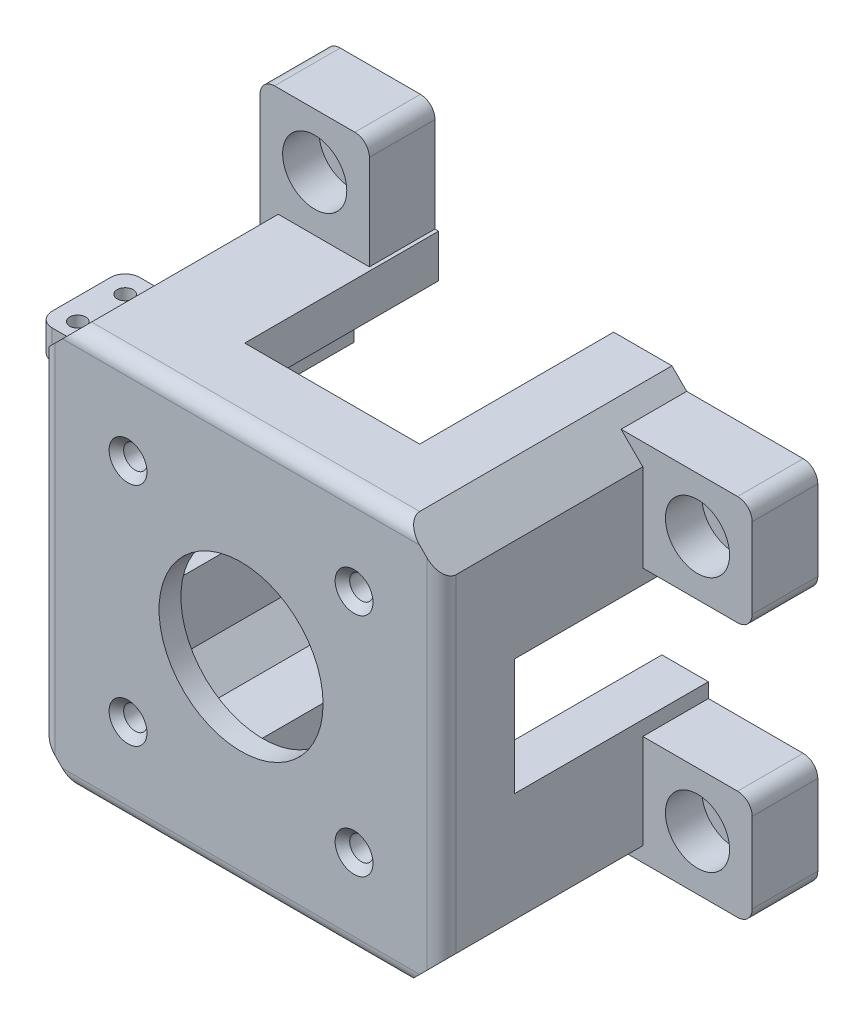
SolidWorks part; units mm, degrees
ref_plane "Front Plane" through (0, 0, 0) normal (0, 0, 1) x (1, 0, 0)
ref_plane "Top Plane" through (0, 0, 0) normal (0, 1, 0) x (1, 0, 0)
ref_plane "Right Plane" through (0, 0, 0) normal (1, 0, 0) x (0, 0, -1)
sketch "Sketch2" plane through (0, 0, 0) normal (0, 0, 1) x (1, 0, 0)
  line L1 (-27.5, -27.0238) -> (27.5, -27.0238)
  line L2 (-27.5, -27.0238) -> (-27.5, 27.9762)
  line L3 (-27.5, 27.9762) -> (27.5, 27.9762)
  line L4 (27.5, -27.0238) -> (27.5, 27.9762)
  line L5 (-27.5, -27.0238) -> (27.5, 27.9762) construction
  line L6 (-27.5, 27.9762) -> (27.5, -27.0238) construction
  line L16 (21.1184, 17.2806) -> (17.2806, 21.1184)
  line L17 (17.2806, 21.1184) -> (-17.2806, 21.1184)
  line L18 (-17.2806, 21.1184) -> (-21.1184, 17.2806)
  line L19 (-21.1184, 17.2806) -> (-21.1184, -17.2806)
  line L20 (-21.1184, -17.2806) -> (-17.2806, -21.1184)
  line L21 (-17.2806, -21.1184) -> (17.2806, -21.1184)
  line L22 (17.2806, -21.1184) -> (21.1184, -17.2806)
  line L23 (21.1184, -17.2806) -> (21.1184, 17.2806)
  circle A2 centre (0, 0.4762) radius 16.593
  dimension "D1" = 55
  dimension "D2" = 55
extrude "Boss-Extrude1" add sketch "Sketch2" along normal blind 33.6 contours L1 L4 L3 L2 L23 L22 L21 L20 L19 L18 L17 L16
sketch "Sketch3" plane through (0, 0, 33.6) normal (0, 0, 1) x (1, 0, 0)
  line L0 (-27.5, 27.9762) -> (27.5, -27.0238)
  line L1 (-27.5, -27.0238) -> (27.5, -27.0238)
  line L2 (-27.5, -27.0238) -> (-27.5, 27.9762)
  line L3 (-27.5, 27.9762) -> (27.5, 27.9762)
  line L4 (27.5, -27.0238) -> (27.5, 27.9762)
  line L5 (27.5, 27.9762) -> (-27.5, -27.0238)
  circle A0 centre (0, 0.4762) radius 11.25
  line M1 (21.1184, 17.2806) -> (21.1184, -17.2806)
  line M2 (21.1184, -17.2806) -> (17.2806, -21.1184)
  line M3 (17.2806, -21.1184) -> (-17.2806, -21.1184)
  line M4 (-17.2806, -21.1184) -> (-21.1184, -17.2806)
  line M5 (-21.1184, -17.2806) -> (-21.1184, 17.2806)
  line M6 (-21.1184, 17.2806) -> (-17.2806, 21.1184)
  line M7 (-17.2806, 21.1184) -> (17.2806, 21.1184)
  line M8 (17.2806, 21.1184) -> (21.1184, 17.2806)
  line M9 (-27.5, -27.0238) -> (27.5, -27.0238)
  line M10 (27.5, -27.0238) -> (27.5, 27.9762)
  line M11 (27.5, 27.9762) -> (-27.5, 27.9762)
  line M12 (-27.5, 27.9762) -> (-27.5, -27.0238)
  dimension "D1" = 22.5
extrude "Boss-Extrude2" add sketch "Sketch3" along normal blind 3 contours A0 L0 L5 M6 M5 M4 | A0 L5 L0 M4 M3 M2 | A0 L0 L5 M2 M1 M8 | A0 L5 L0 M8 M7 M6 | L5 L0 M4 M5 M6 M12 | L5 L0 M4 M9 M2 M3 | L5 L0 M10 M8 M1 M2 | L5 L0 M11 M6 M7 M8
sketch "Sketch4" plane through (0, 0, 0) normal (0, 0, -1) x (-1, 0, 0)
  line L0 (0, 0) -> (-27.5, 0)
  line L1 (-27.5, -27.0238) -> (-27.5, 27.9762) construction
  line L2 (-27.5, 0) -> (-27.5, 10)
  line L3 (0, 0) -> (0, 34.2278) construction
  line L4 (-27.5, 10) -> (-42.5, 10)
  line L5 (-27.5, 10) -> (-27.5, 25)
  line L6 (-27.5, 25) -> (-42.5, 25)
  line L7 (-42.5, 10) -> (-42.5, 25)
  line L8 (42.5, 10) -> (42.5, 25)
  line L9 (27.5, 25) -> (42.5, 25)
  line L10 (27.5, 10) -> (27.5, 25)
  line L11 (27.5, 10) -> (42.5, 10)
  line L16 (-42.5, -10) -> (-42.5, -25)
  line L17 (-27.5, -25) -> (-42.5, -25)
  line L18 (-27.5, -10) -> (-27.5, -25)
  line L19 (-27.5, -10) -> (-42.5, -10)
  line L20 (27.5, -27.0238) -> (-27.5, -27.0238) construction
  line L21 (25, -27.0238) -> (10, -27.0238)
  line L22 (25, -27.0238) -> (25, -42.0238)
  line L23 (25, -42.0238) -> (10, -42.0238)
  line L24 (10, -27.0238) -> (10, -42.0238)
  circle A1 centre (-35, 17.5) radius 2.6
  circle A2 centre (35, 17.5) radius 2.6
  circle A4 centre (-35, -17.5) radius 2.6
  circle A5 centre (17.5, -34.5238) radius 2.6
  dimension "D1" = 10
  dimension "D4" = 5.2
  dimension "D5" = 7.5
  dimension "D10" = 5.2
  dimension "D2" = 15
  dimension "D3" = 15
  dimension "D6" = 7.5
  dimension "D7" = 15
  dimension "D8" = 15
  dimension "D9" = 10
  dimension "D11" = 7.5
  dimension "D12" = 7.5
extrude "Boss-Extrude3" add sketch "Sketch4" against normal blind 9 contours L7 L4 L11 L6 A1 | L11 L19 L16 L17 A4 | A5 | A2 | L22 L23 L24 L21
sketch "Sketch6" plane through (0, 0, 9) normal (0, 0, 1) x (1, 0, 0)
  line L2 (20.955, 0) -> (-20.955, 0) construction
  line L7 (-10, -27.0238) -> (-25, -27.0238)
  line L8 (-25, -27.0238) -> (-25, -42.0238)
  line L9 (-25, -42.0238) -> (-10, -42.0238)
  line L10 (-10, -42.0238) -> (-10, -27.0238)
  line L11 (-10, -27.0238) -> (-25, -27.0238)
  line L12 (-25, -27.0238) -> (-25, -42.0238)
  line L13 (-25, -42.0238) -> (-10, -42.0238)
  line L14 (-10, -42.0238) -> (-10, -27.0238)
  circle A0 centre (35, -17.5) radius 4.4
  circle A2 centre (35, 17.5) radius 4.4
  circle A3 centre (-35, 17.5) radius 4.4
  circle A4 centre (-17.5, -34.5238) radius 4.4
  circle M5 centre (35, -17.5) radius 2.6
  dimension "D1" = 8.8
  dimension "D3" = 8.8
  dimension "D2" = 0
extrude "Cut-Extrude1" cut sketch "Sketch6" against normal blind 5 contours A4 | A3 | A0 M5 | A2
chamfer "Chamfer1" distance 5 angle 45 4 edges at (27.5, -27.0238, 18.3) (-27.5, -27.0238, 18.3) (27.5, 27.9762, 18.3) (-27.5, 27.9762, 18.3)
fillet "Fillet4" radius 2 12 edges at (42.5, -10, 4.5) (42.5, -25, 4.5) (42.5, 10, 4.5) (42.5, 25, 4.5) (-42.5, 10, 4.5) (-42.5, 25, 4.5) (0, -27.0238, 36.6) (-27.5, 0.4762, 36.6) (27.5, 0.4762, 36.6) (0, 27.9762, 36.6) (-25, -42.0238, 4.5) (-10, -42.0238, 4.5)
sketch "Sketch7" plane through (0, -27.0238, 0) normal (0, -1, 0) x (1, 0, 0)
  line L0 (-10, 0) -> (22.5, 0) construction
  line L1 (-9.5, 0) -> (14.5, 0)
  line L2 (-9.5, 0) -> (-9.5, 26.6)
  line L3 (-9.5, 26.6) -> (14.5, 26.6)
  line L4 (14.5, 0) -> (14.5, 26.6)
  line L5 (22.5, 0) -> (22.5, 34.6) construction
  line L6 (-22.5, 34.6) -> (-22.5, 9) construction
  line L7 (22.5, 34.6) -> (-22.5, 34.6) construction
  dimension "D1" = 8
  dimension "D2" = 13
  dimension "D3" = 8
extrude "Cut-Extrude2" cut sketch "Sketch7" against normal blind 67
sketch "Sketch8" plane through (-27.5, 0, 0) normal (-1, 0, 0) x (0, 0, 1)
  line L0 (34.6, -22.0238) -> (34.6, 22.9762) construction
  line L1 (0, 8) -> (26.6, 8)
  line L2 (0, 8) -> (0, -8)
  line L3 (0, -8) -> (26.6, -8)
  line L4 (26.6, 8) -> (26.6, -8)
  dimension "D1" = 8
  dimension "D2" = 16
  dimension "D3" = 26.6
  dimension "D4" = 8
extrude "Cut-Extrude3" cut sketch "Sketch8" against normal blind 67
sketch "Sketch9" plane through (0, 0, 0) normal (0, 0, -1) x (-1, 0, 0)
  line L0 (-21.1184, -17.2806) -> (-21.1184, -8) construction
  line L1 (-21.1184, -8) -> (-27.5, -8) construction
  line L2 (-27.5, -8) -> (-27.5, -10) construction
  line L3 (-27.5, -10) -> (-40.5, -10) construction
  line L4 (-42.5, -12) -> (-42.5, -23) construction
  line L5 (-40.5, -25) -> (-24.5238, -25) construction
  line L6 (-24.5238, -25) -> (-22.5, -27.0238) construction
  line L7 (-22.5, -27.0238) -> (-14.5, -27.0238) construction
  line L8 (-14.5, -27.0238) -> (-14.5, -21.1184) construction
  line L9 (-14.5, -21.1184) -> (-17.2806, -21.1184) construction
  line L10 (-17.2806, -21.1184) -> (-21.1184, -17.2806) construction
  line L11 (27.5, -22.0238) -> (27.5, -8) construction
  line L12 (27.5, -8) -> (21.1184, -8) construction
  line L13 (21.1184, -8) -> (21.1184, -17.2806) construction
  line L14 (21.1184, -17.2806) -> (17.2806, -21.1184) construction
  line L15 (17.2806, -21.1184) -> (9.5, -21.1184) construction
  line L16 (9.5, -21.1184) -> (9.5, -27.0238) construction
  line L17 (9.5, -27.0238) -> (10, -27.0238) construction
  line L18 (10, -27.0238) -> (10, -40.0238) construction
  line L19 (12, -42.0238) -> (23, -42.0238) construction
  line L20 (25, -40.0238) -> (25, -24.5238) construction
  line L21 (25, -24.5238) -> (27.5, -22.0238) construction
  line L22 (21.1184, 17.2806) -> (21.1184, 8) construction
  line L23 (21.1184, 8) -> (27.5, 8) construction
  line L24 (27.5, 8) -> (27.5, 10) construction
  line L25 (27.5, 10) -> (40.5, 10) construction
  line L26 (42.5, 12) -> (42.5, 23) construction
  line L27 (40.5, 25) -> (25.4762, 25) construction
  line L28 (25.4762, 25) -> (22.5, 27.9762) construction
  line L29 (22.5, 27.9762) -> (9.5, 27.9762) construction
  line L30 (9.5, 27.9762) -> (9.5, 21.1184) construction
  line L31 (9.5, 21.1184) -> (17.2806, 21.1184) construction
  line L32 (17.2806, 21.1184) -> (21.1184, 17.2806) construction
  line L33 (-27.5, 10) -> (-27.5, 8) construction
  line L34 (-27.5, 8) -> (-21.1184, 8) construction
  line L35 (-21.1184, 8) -> (-21.1184, 17.2806) construction
  line L36 (-21.1184, 17.2806) -> (-17.2806, 21.1184) construction
  line L37 (-17.2806, 21.1184) -> (-14.5, 21.1184) construction
  line L38 (-14.5, 21.1184) -> (-14.5, 27.9762) construction
  line L39 (-14.5, 27.9762) -> (-22.5, 27.9762) construction
  line L40 (-22.5, 27.9762) -> (-25.4762, 25) construction
  line L41 (-25.4762, 25) -> (-40.5, 25) construction
  line L42 (-42.5, 23) -> (-42.5, 12) construction
  line L43 (-40.5, 10) -> (-27.5, 10) construction
  line L44 (-21.1184, -17.2806) -> (-21.1184, -8)
  line L45 (-21.1184, -8) -> (-27.5, -8)
  line L46 (-27.5, -8) -> (-27.5, -10)
  line L47 (-27.5, -10) -> (-40.5, -10)
  line L48 (-42.5, -12) -> (-42.5, -23)
  line L49 (-40.5, -25) -> (-24.5238, -25)
  line L50 (-24.5238, -25) -> (-22.5, -27.0238)
  line L51 (-22.5, -27.0238) -> (-14.5, -27.0238)
  line L52 (-14.5, -27.0238) -> (-14.5, -21.1184)
  line L53 (-14.5, -21.1184) -> (-17.2806, -21.1184)
  line L54 (-17.2806, -21.1184) -> (-21.1184, -17.2806)
  line L55 (27.5, -22.0238) -> (27.5, -8)
  line L56 (27.5, -8) -> (21.1184, -8)
  line L57 (21.1184, -8) -> (21.1184, -17.2806)
  line L58 (21.1184, -17.2806) -> (17.2806, -21.1184)
  line L59 (17.2806, -21.1184) -> (9.5, -21.1184)
  line L60 (9.5, -21.1184) -> (9.5, -27.0238)
  line L61 (9.5, -27.0238) -> (10, -27.0238)
  line L62 (10, -27.0238) -> (10, -40.0238)
  line L63 (12, -42.0238) -> (23, -42.0238)
  line L64 (25, -40.0238) -> (25, -24.5238)
  line L65 (25, -24.5238) -> (27.5, -22.0238)
  line L66 (21.1184, 17.2806) -> (21.1184, 8)
  line L67 (21.1184, 8) -> (27.5, 8)
  line L68 (27.5, 8) -> (27.5, 10)
  line L69 (27.5, 10) -> (40.5, 10)
  line L70 (42.5, 12) -> (42.5, 23)
  line L71 (40.5, 25) -> (25.4762, 25)
  line L72 (25.4762, 25) -> (22.5, 27.9762)
  line L73 (22.5, 27.9762) -> (9.5, 27.9762)
  line L74 (9.5, 27.9762) -> (9.5, 21.1184)
  line L75 (9.5, 21.1184) -> (17.2806, 21.1184)
  line L76 (17.2806, 21.1184) -> (21.1184, 17.2806)
  line L77 (-27.5, 10) -> (-27.5, 8)
  line L78 (-27.5, 8) -> (-21.1184, 8)
  line L79 (-21.1184, 8) -> (-21.1184, 17.2806)
  line L80 (-21.1184, 17.2806) -> (-17.2806, 21.1184)
  line L81 (-17.2806, 21.1184) -> (-14.5, 21.1184)
  line L82 (-14.5, 21.1184) -> (-14.5, 27.9762)
  line L83 (-14.5, 27.9762) -> (-22.5, 27.9762)
  line L84 (-22.5, 27.9762) -> (-25.4762, 25)
  line L85 (-25.4762, 25) -> (-40.5, 25)
  line L86 (-42.5, 23) -> (-42.5, 12)
  line L87 (-40.5, 10) -> (-27.5, 10)
  arc A0 (-40.5, -10) -> (-42.5, -12) centre (-40.5, -12) ccw construction
  arc A1 (-42.5, -23) -> (-40.5, -25) centre (-40.5, -23) ccw construction
  arc A2 (10, -40.0238) -> (12, -42.0238) centre (12, -40.0238) ccw construction
  arc A3 (23, -42.0238) -> (25, -40.0238) centre (23, -40.0238) ccw construction
  arc A4 (40.5, 10) -> (42.5, 12) centre (40.5, 12) ccw construction
  arc A5 (42.5, 23) -> (40.5, 25) centre (40.5, 23) ccw construction
  arc A6 (-40.5, 25) -> (-42.5, 23) centre (-40.5, 23) ccw construction
  arc A7 (-42.5, 12) -> (-40.5, 10) centre (-40.5, 12) ccw construction
  arc A8 (-40.5, -10) -> (-42.5, -12) centre (-40.5, -12) ccw
  arc A9 (-42.5, -23) -> (-40.5, -25) centre (-40.5, -23) ccw
  arc A10 (10, -40.0238) -> (12, -42.0238) centre (12, -40.0238) ccw
  arc A11 (23, -42.0238) -> (25, -40.0238) centre (23, -40.0238) ccw
  arc A12 (40.5, 10) -> (42.5, 12) centre (40.5, 12) ccw
  arc A13 (42.5, 23) -> (40.5, 25) centre (40.5, 23) ccw
  arc A14 (-40.5, 25) -> (-42.5, 23) centre (-40.5, 23) ccw
  arc A15 (-42.5, 12) -> (-40.5, 10) centre (-40.5, 12) ccw
mirror "Mirror2" about plane through (-25, -42.0238, 9) normal (0, 1, 0) of bodies 107
delete or keep bodies "Body-Delete/Keep 1" type delete bodies bodies 107
sketch "Sketch11" plane through (-27.5, 0, 0) normal (-1, 0, 0) x (0, 0, 1)
  line L0 (0, -65.0238) -> (34.6, -65.0238) construction
  line L1 (0, -62.0238) -> (0, -76.0476) construction
  line L2 (34.6, -62.0238) -> (34.6, -107.0238) construction
  line L3 (0, -62.0238) -> (34.6, -62.0238) construction
  line L5 (20, -67.0238) -> (32, -67.0238)
  line L6 (20, -67.0238) -> (20, -63.0238)
  line L7 (20, -63.0238) -> (32, -63.0238)
  line L8 (32, -67.0238) -> (32, -63.0238)
  line L9 (20, -67.0238) -> (32, -63.0238) construction
  line L10 (20, -63.0238) -> (32, -67.0238) construction
  point P8 (26, -65.0238)
  dimension "D1" = 3
  dimension "D2" = 4
  dimension "D3" = 12
  dimension "D4" = 26
extrude "Boss-Extrude4" add sketch "Sketch11" along normal blind 5 and the other way up to next
sketch "Sketch12" plane through (0, -67.0238, 0) normal (0, -1, 0) x (1, 0, 0)
  line L0 (-32.5, 32) -> (-27.5, 32) construction
  line L2 (-32.5, 20) -> (-32.5, 32) construction
  circle A0 centre (-29.5, 29.5) radius 1.1
  circle A1 centre (-29.5, 23) radius 1.1
  dimension "D1" = 2.2
  dimension "D2" = 6.5
  dimension "D3" = 2.5
  dimension "D4" = 3
  dimension "D5" = 3
extrude "Cut-Extrude5" cut sketch "Sketch12" against normal up to surface (4 mm away) up to face at (-30, -63.0238, 26)
fillet "Fillet8" radius 2 2 edges at (-32.5, -65.0238, 32) (-32.5, -65.0238, 20)
sketch "Sketch13" plane through (0, 0, 36.6) normal (0, 0, 1) x (1, 0, 0)
  line L1 (-15.5, -100.0238) -> (15.5, -100.0238) construction
  line L2 (-15.5, -100.0238) -> (-15.5, -69.0238) construction
  line L3 (-15.5, -69.0238) -> (15.5, -69.0238) construction
  line L4 (15.5, -100.0238) -> (15.5, -69.0238) construction
  line L5 (-15.5, -100.0238) -> (15.5, -69.0238) construction
  line L6 (-15.5, -69.0238) -> (15.5, -100.0238) construction
  circle A0 centre (15.5, -100.0238) radius 1.6
  circle A1 centre (-15.5, -100.0238) radius 1.6
  circle A2 centre (-15.5, -69.0238) radius 1.6
  circle A3 centre (15.5, -69.0238) radius 1.6
  point P0 (0, -84.5238)
  dimension "D3" = 3.2
  dimension "D1" = 31
  dimension "D2" = 31
extrude "Cut-Extrude6" cut sketch "Sketch13" against normal blind 10
chamfer "Chamfer2" distance 1 angle 45 4 edges at (17.1, -69.0238, 36.6) (-13.9, -69.0238, 36.6) (-13.9, -100.0238, 36.6) (17.1, -100.0238, 36.6)
